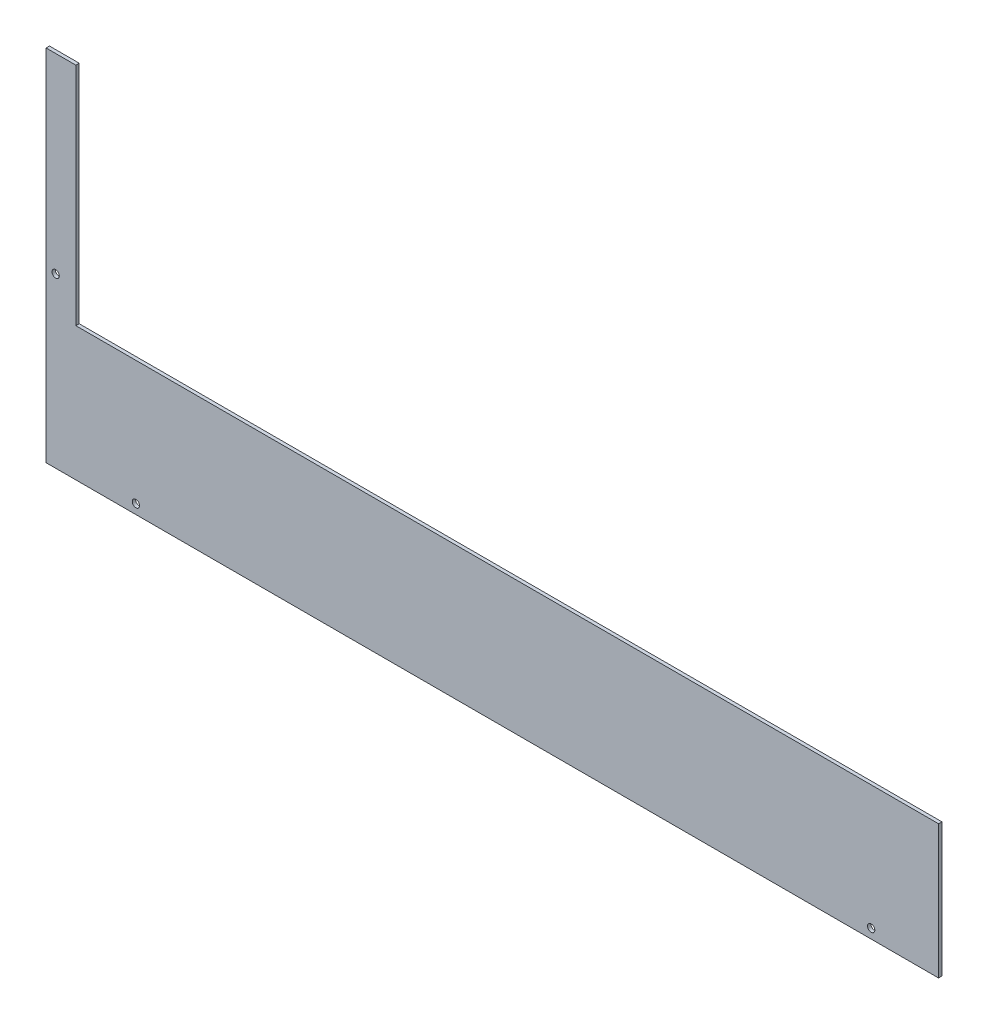
SolidWorks part; units mm, degrees
ref_plane "정면" through (0, 0, 0) normal (0, 0, 1) x (1, 0, 0)
ref_plane "윗면" through (0, 0, 0) normal (0, 1, 0) x (1, 0, 0)
ref_plane "우측면" through (0, 0, 0) normal (1, 0, 0) x (0, 0, -1)
sketch "스케치1" plane through (0, 0, 0) normal (0, 0, 1) x (1, 0, 0)
  line L1 (0, 0) -> (26.5, 0)
  line L4 (26.5, 0) -> (26.5, -201)
  line L5 (0, -320) -> (795, -320)
  line L6 (0, -320) -> (0, 0)
  line L7 (26.5, -201) -> (795, -201)
  line L8 (795, -320) -> (795, -201)
  circle A0 centre (735, -311.5) radius 3.25
  circle A1 centre (80, -311.5) radius 3.25
  circle A2 centre (8.5, -170) radius 3.25
  point P13 (0, 0)
  point P14 (0, 0)
  point P15 (0, 0)
  dimension "D10" = 6.5
  dimension "D1" = 795
  dimension "D2" = 320
  dimension "D3" = 768.5
  dimension "D4" = 119
  dimension "D5" = 8.5
  dimension "D6" = 141.5
  dimension "D7" = 8.5
  dimension "D8" = 71.5
  dimension "D9" = 655
extrude "보스-돌출1" add sketch "스케치1" along normal blind 3
